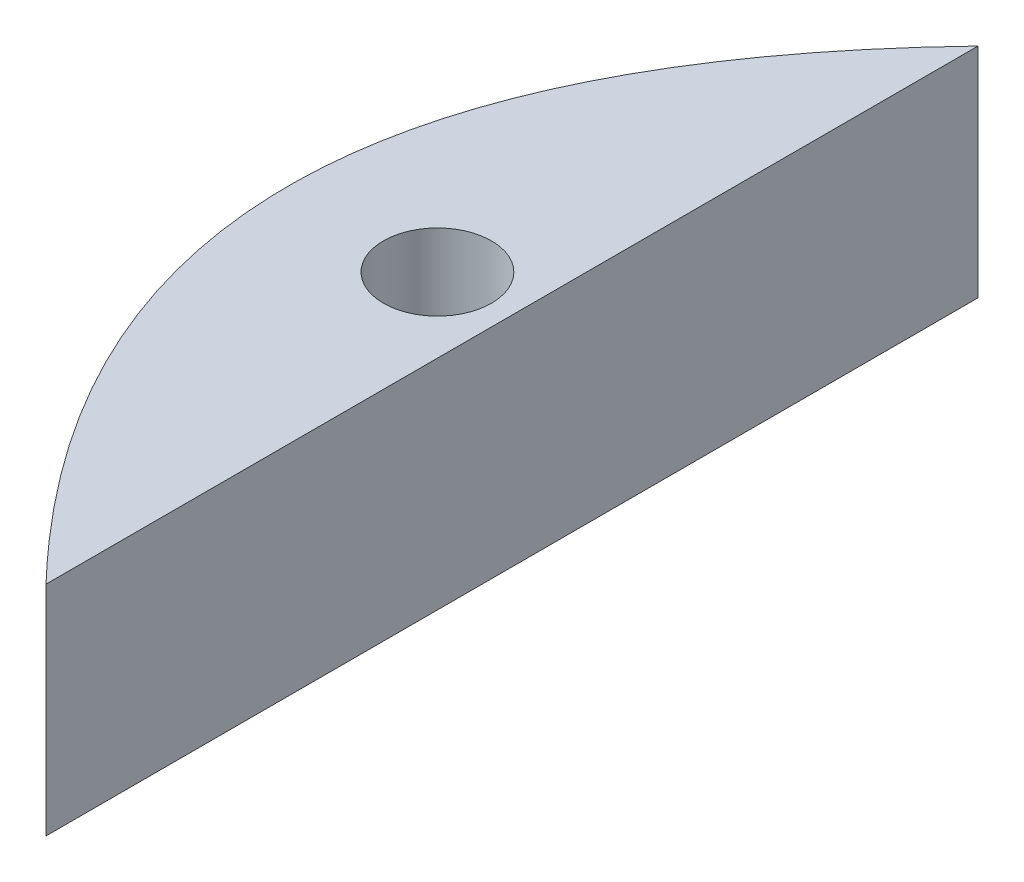
SolidWorks part; units mm, degrees
material "Acrylic (Medium-high impact)"
ref_plane "Front Plane" through (0, 0, 0) normal (0, 0, 1) x (1, 0, 0)
ref_plane "Top Plane" through (0, 0, 0) normal (0, 1, 0) x (1, 0, 0)
ref_plane "Right Plane" through (0, 0, 0) normal (1, 0, 0) x (0, 0, -1)
sketch "Sketch1" plane through (0, 0, 0) normal (0, 1, 0) x (1, 0, 0)
  line L0 (-1000, 0) -> (49000, 0) construction
  line L1 (0, -1000) -> (0, 49000) construction
  line L2 (2, 12.5) -> (2, -12.5)
  circle A0 centre (0, 0) radius 1.45
  spline S0 degree 2 poles (2, 12.5) (-10, 0) (2, -12.5) knots 0 0 0 1 1 1
  dimension "D1" = 2.9
  dimension "D4" = 4
  dimension "D2" = 2
  dimension "D3" = 25
extrude "Boss-Extrude1" add sketch "Sketch1" along normal blind 5.85
